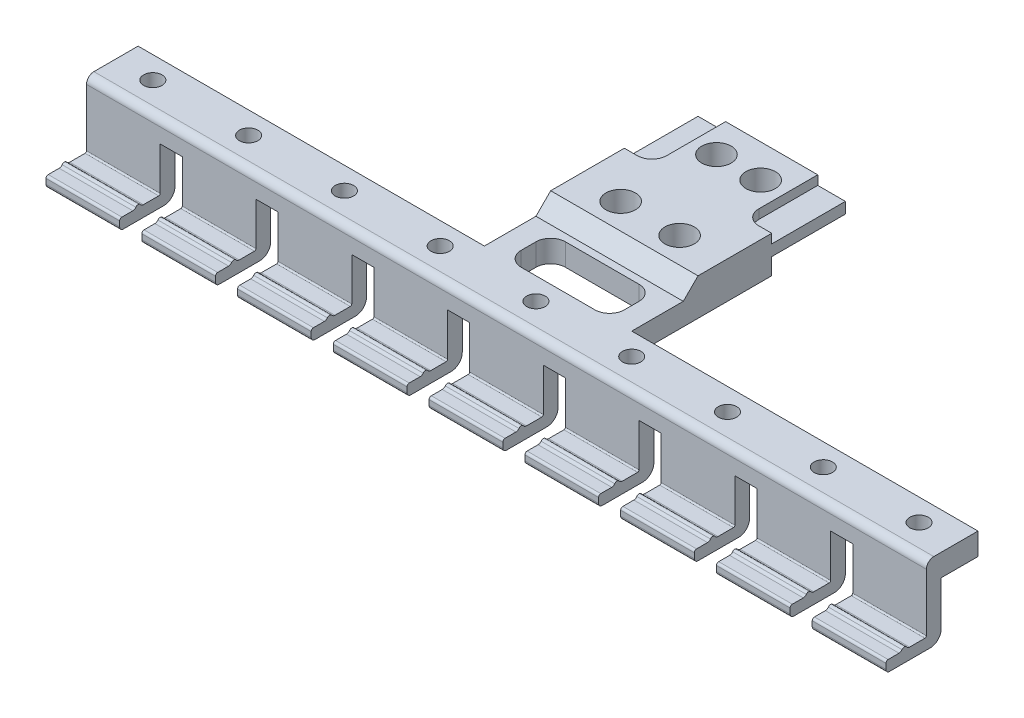
SolidWorks part; units mm, degrees
material "AISI 316"
ref_plane "Front Plane" through (0, 0, 0) normal (0, 0, 1) x (1, 0, 0)
ref_plane "Top Plane" through (0, 0, 0) normal (0, 1, 0) x (1, 0, 0)
ref_plane "Right Plane" through (0, 0, 0) normal (1, 0, 0) x (0, 0, -1)
sketch "Sketch1" plane through (0, 0, 0) normal (0, 0, 1) x (1, 0, 0)
  line L1 (-57, -6) -> (57, -6)
  line L2 (-57, -6) -> (-57, 0)
  line L3 (-57, 0) -> (57, 0)
  line L4 (57, -6) -> (57, 0)
  line L5 (-57, -6) -> (57, 0) construction
  line L6 (-57, 0) -> (57, -6) construction
  point P0 (0, -3)
  dimension "D1" = 6
  dimension "D2" = 114
extrude "Boss-Extrude1" add sketch "Sketch1" along normal blind 4 contours L3 L4 L1 L2
sketch "Sketch2" plane through (0, 0, 0) normal (0, 0, 1) x (1, 0, 0)
  line L1 (-10, -6) -> (10, -6)
  line L2 (-10, -6) -> (-10, 0)
  line L3 (-10, 0) -> (10, 0)
  line L4 (10, -6) -> (10, 0)
  line L5 (-10, -6) -> (10, 0) construction
  line L6 (-10, 0) -> (10, -6) construction
  point P0 (0, -3)
  dimension "D1" = 20
  dimension "D2" = 6
extrude "Boss-Extrude2" add sketch "Sketch2" against normal blind 22
sketch "Sketch3" plane through (0, 0, -22) normal (0, 0, -1) x (-1, 0, 0)
  line L0 (10, 0) -> (10, -6) construction
  line L1 (-6.25, -5) -> (6.25, -5)
  line L2 (-6.25, -5) -> (-6.25, -3.75)
  line L3 (-6.25, -1) -> (6.25, -1)
  line L4 (6.25, -5) -> (6.25, -3.75)
  line L7 (-10, -3.75) -> (-6.25, -3.75)
  line L8 (-10, -3.75) -> (-10, -2.25)
  line L9 (-10, -2.25) -> (-6.25, -2.25)
  line L10 (10, -3.75) -> (10, -2.25)
  line L14 (10, -6) -> (-10, -6) construction
  line L15 (-6.25, -2.25) -> (-6.25, -1)
  line L18 (6.25, -2.25) -> (10, -2.25)
  line L20 (6.25, -2.25) -> (6.25, -1)
  line L21 (6.25, -3.75) -> (10, -3.75)
  point P0 (0, -3)
  point P7 (0, -3)
  point P14 (-10, -3)
  dimension "D1" = 12.5
  dimension "D2" = 1.5
  dimension "D3" = 4
  dimension "D4" = 1
  dimension "D5" = 3.75
extrude "Boss-Extrude3" add sketch "Sketch3" along normal blind 10 contours L7 L2 L1 L4 L21 L10 L18 L20 L3 L15 L9 L8
sketch "Sketch4" plane through (0, -1, 0) normal (0, 1, 0) x (1, 0, 0)
  line L0 (6.25, 32) -> (-6.25, 32) construction
  circle A0 centre (-3, 27.5) radius 2
  circle A1 centre (3, 27.5) radius 2
  point P13 (0, 32)
  dimension "D3" = 4
  dimension "D6" = 4
  dimension "D1" = 4.5
  dimension "D2" = 3
  dimension "D4" = 3
extrude "Cut-Extrude1" cut sketch "Sketch4" against normal through all
sketch "Sketch8" plane through (0, 0, 0) normal (0, 1, 0) x (1, 0, 0)
  line L5 (10, 22) -> (-10, 22) construction
  line L11 (-5.5, 14) -> (-2.5, 17) construction
  line L12 (-5.5, 17) -> (-2.5, 14) construction
  circle A0 centre (-4, 15.5) radius 2
  circle A1 centre (4, 15.5) radius 2
  point P5 (-4, 15.5)
  dimension "D5" = 4
  dimension "D6" = 4
  dimension "D1" = 6.5
  dimension "D2" = 8
  dimension "D3" = 4
  dimension "D4" = 6.5
extrude "Cut-Extrude3" cut sketch "Sketch8" against normal through all
sketch "Sketch6" plane through (0, 0, 0) normal (0, 1, 0) x (1, 0, 0)
  line L1 (-7, 3) -> (7, 3)
  line L2 (-7, 3) -> (-7, 9)
  line L3 (-7, 9) -> (7, 9)
  line L4 (7, 3) -> (7, 9)
  point P4 (0, 9)
  dimension "D1" = 14
  dimension "D2" = 6
  dimension "D3" = 3
extrude "Cut-Extrude2" cut sketch "Sketch6" against normal blind 10
fillet "Fillet5" radius 2 4 edges at (-7, -3, -3) (7, -3, -3) (-7, -3, -9) (7, -3, -9)
sketch "Sketch10" plane through (0, 0, 0) normal (1, 0, 0) x (0, 0, -1)
  line L0 (10, -3) -> (12, -1)
  line L1 (-4, 0) -> (9.5, 0)
  line L2 (-4, 0) -> (-4, -3)
  line L3 (-4, -3) -> (10, -3)
  line L5 (22, 0) -> (0, 0) construction
  line L6 (13, 0) -> (9.5, 0)
  line L7 (22, -1) -> (12, -1)
  line L8 (32, -1) -> (22, -1) construction
  line L9 (22, -2.25) -> (22, 0) construction
  line L10 (13, 0) -> (22, 0)
  line L11 (22, 0) -> (22, -1)
  dimension "D1" = 14
  dimension "D2" = 3
  dimension "D3" = 45
extrude "Cut-Extrude5" cut sketch "Sketch10" against normal through all both and the other way through all
sketch "Sketch11" plane through (0, 0, 0) normal (1, 0, 0) x (0, 0, -1)
  line L0 (22, -6) -> (0, -6) construction
  line L1 (0, -3) -> (3, -3)
  line L2 (0, -3) -> (0, -6)
  line L3 (0, -6) -> (3, -6)
  line L4 (3, -3) -> (3, -6)
  line L5 (-4, -6) -> (-4, -3) construction
  dimension "D1" = 7
extrude "Boss-Extrude5" add sketch "Sketch11" along normal up to surface and the other way up to surface up to face at (57, -4.5, 2) other way up to face at (-57, -4.5, 2)
sketch "Sketch5" plane through (-57, 0, 0) normal (-1, 0, 0) x (0, 0, 1)
  line L0 (3.5, -13.5) -> (9, -13.5)
  line L4 (4, -6) -> (4, -11.8)
  line L13 (4, -6) -> (4, -3) construction
  line L14 (9.5, -13) -> (9.5, -12.3)
  line L15 (9.2, -12) -> (7.375, -12)
  line L16 (7.375, -12) -> (6.625, -12) construction
  line L17 (6.625, -12) -> (4.2, -12)
  line L19 (2, -6) -> (4, -6)
  line L20 (4, -6) -> (-3, -6) construction
  line L21 (2, -6) -> (2, -12)
  arc A0 (7.375, -12) -> (6.625, -12) centre (7, -12) ccw
  arc A1 (6.625, -12) -> (7.375, -12) centre (7, -12) ccw construction
  arc A3 (9, -13.5) -> (9.5, -13) centre (9, -13) ccw
  arc A4 (2, -12) -> (3.5, -13.5) centre (3.5, -12) ccw
  arc A5 (4, -11.8) -> (4.2, -12) centre (4.2, -11.8) ccw
  arc A6 (9.5, -12.3) -> (9.2, -12) centre (9.2, -12.3) ccw
  point P9 (9.5, -12.65)
  point P16 (9.5, -12)
  point P19 (9.5, -13.5)
  dimension "D3" = 0.75
  dimension "D6" = 1.5
  dimension "D7" = 0.5
  dimension "D8" = 0.2
  dimension "D10" = 0.3
  dimension "D1" = 5.5
  dimension "D2" = 2.5
  dimension "D4" = 1.5
  dimension "D5" = 2
  dimension "D9" = 6
extrude "Boss-Extrude4" add sketch "Sketch5" against normal blind 10
fillet "Fillet10" radius 0.5 2 edges at (-52, -12, 6.625) (-52, -12, 7.375)
hole_wizard "M3 Tapped Hole1" positions "Sketch12" profile "Sketch13" tap size "M3" standard "ISO" end condition through all
sketch "Sketch12" plane through (0, -3, 0) normal (0, 1, 0) x (1, 0, 0)
  point P0 (-52, 0)
sketch "Sketch13" plane through (-52, -3, 0) normal (1, 0, 0) x (0, 0, 1)
  line L0 (0, 0) -> (0, 10.5)
  line L1 (0, 10.5) -> (1.25, 10.5)
  line L2 (1.25, 10.5) -> (1.25, 0)
  line L5 (1.25, 0) -> (0, 0)
  line L11 (0, -6.35) -> (0, 107.95) construction
  dimension "Thru Tap Drill Dia." = 2.5
  dimension "Thru Tap Drill Depth" = 10.5
thread "Thread1" [suppressed] pitch 0.5 start angle 0, offset 0, length 0, pitch 0.5, diameter 2.5
ref_plane "Plane3" through (-53.25, -3, 0) normal (0, 0, 1) x (-1, 0, 0)
sketch "Thread Profile1" plane through (-53.25, -3, 0) normal (0, 0, 1) x (-1, 0, 0)
  line L0 (0, 0) -> (0, 0.5) construction
  line L1 (0, 0) -> (0.2706, 0.1562)
  line L2 (0.2706, 0.1562) -> (0.2706, 0.2187)
  line L3 (0.2706, 0.2187) -> (0, 0.375)
  line L4 (0.2706, 0.1875) -> (0, 0.1875) construction
  line L11 (0, 0) -> (0, 0.375)
  point P2 (0, 0)
  dimension "Pitch" = 0.5
  dimension "Profile_Angle" = 60
  dimension "Profile_Land" = 0.0625
  dimension "Profile_Height" = 0.2706
pattern_linear "LPattern1" count 9 spacing 13 along (1, 0, 0) of "Boss-Extrude4", "Fillet10", "M3 Tapped Hole1", "Thread1"
fillet "Fillet11" radius 1 1 edges at (0, -3, 4)
fillet "Fillet4" [suppressed] radius 1
ref_plane "Plane2" through (-47, 0, 0) normal (-1, 0, 0) x (0, 0, 1)
fillet "Fillet12" radius 2 4 edges at (6.25, -4.375, -22) (6.25, -1.625, -22) (-6.25, -4.375, -22) (-6.25, -1.625, -22)
